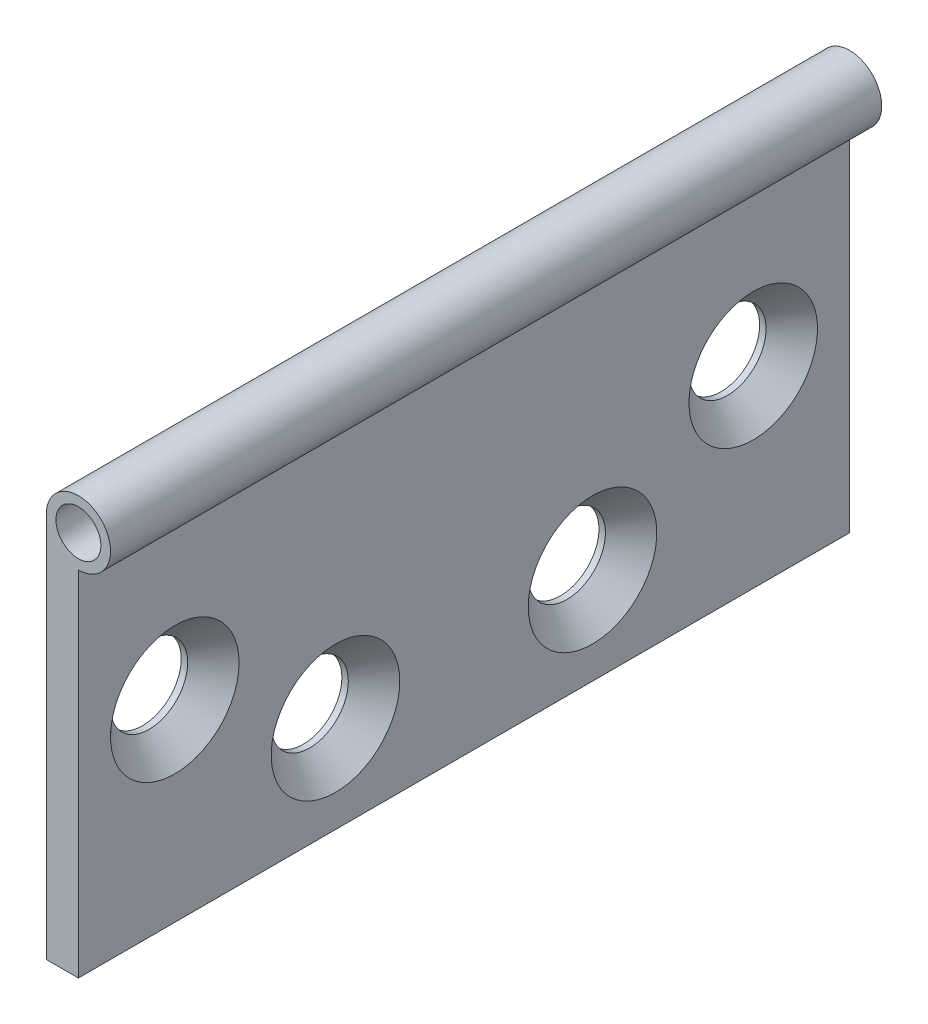
SolidWorks part; units mm, degrees
ref_plane "Спереди" through (0, 0, 0) normal (0, 0, 1) x (1, 0, 0)
ref_plane "Сверху" through (0, 0, 0) normal (0, 1, 0) x (1, 0, 0)
ref_plane "Справа" through (0, 0, 0) normal (1, 0, 0) x (0, 0, -1)
sketch "Эскиз1" plane through (0, 0, 0) normal (0, 0, 1) x (1, 0, 0)
  line L0 (0, 0) -> (0, 60)
  dimension "D1" = 60
extrude "Вытянуть-Тонкостенный2" add sketch "Эскиз1" along normal mid plane 120 thin contours L0
sketch "Эскиз2" plane through (0, 0, 60) normal (0, 0, 1) x (1, 0, 0)
  circle A0 centre (5, 60) radius 5
sweep "По траектории1" add profiles "Эскиз2" path edge at (0, 60, 0)
sketch "Эскиз3" plane through (0, 0, 60) normal (0, 0, 1) x (1, 0, 0)
  circle A0 centre (5, 60) radius 3.5
  dimension "D1" = 7
extrude "Вырез-Вытянуть1" cut sketch "Эскиз3" against normal through all
hole_wizard "Зенковка для  винта с плоской головкой M101" positions "Эскиз7" profile "Эскиз8" countersink size "M10" standard "Ansi Metric" end condition through all
sketch "Эскиз7" plane through (5, 0, 0) normal (1, 0, 0) x (0, 0, -1)
  line L0 (-60, 0) -> (-60, 55) construction
  line L1 (-60, 0) -> (60, 0) construction
  point P0 (-45, 30)
  point P2 (-20, 15)
  point P9 (0, 0)
  dimension "D1" = 15
  dimension "D2" = 30
  dimension "D3" = 40
  dimension "D4" = 15
sketch "Эскиз8" plane through (5, 30, 45) normal (0, 1, 0) x (0, 0, -1)
  line L0 (0, 0) -> (0, 5)
  line L1 (0, 5) -> (6, 5)
  line L2 (6, 5) -> (6, 4)
  line L3 (6, 4) -> (10, 0)
  line L5 (10, 0) -> (0, 0)
  line L6 (-6, 4) -> (-10, 0) construction
  line L11 (0, -6.35) -> (0, 107.95) construction
  dimension "Диаметр сквозного отверстия" = 12
  dimension "Глубина сквозного отверстия" = 5
  dimension "Диаметр передней зенковки" = 20
  dimension "Угол передней зенковки" = 90
mirror "Зеркальное отражение1" about plane through (0, 0, 0) normal (0, 0, 1) of "Зенковка для  винта с плоской головкой M101"
sketch "Эскиз10" plane through (5, 0, 0) normal (1, 0, 0) x (0, 0, -1)
  line L0 (-36, 54) -> (-36, 65)
  line L1 (60, 60) -> (60, 65) construction
  line L2 (-60, 54) -> (60, 54)
  line L3 (-60, 54) -> (60, 54)
  line L4 (60, 55) -> (60, 60) construction
  line L5 (-60, 65) -> (-60, 60) construction
  line L6 (-60, 60) -> (-60, 55) construction
  line L7 (60, 60) -> (60, 65)
  line L8 (60, 54) -> (60, 60)
  line L9 (-60, 65) -> (-60, 60)
  line L10 (-60, 60) -> (-60, 54)
  line L11 (-60, 65) -> (60, 65)
  line L12 (-12, 54) -> (-12, 65)
  line L13 (0, 0) -> (0, 65) construction
  line L14 (12, 54) -> (12, 65)
  line L15 (36, 54) -> (36, 65)
  dimension "D2" = 24
  dimension "D3" = 24
  dimension "D1" = 1
equation "\"depth\"= 5"
equation "\"width\"= 60"
equation "\"length\"= 120"
equation "\"D1@Вытянуть-Тонкостенный2\"= \"length\""
equation "\"D1@Эскиз1\"= \"width\""
equation "\"D5@Вытянуть-Тонкостенный2\"= \"depth\""
equation "\"D1@Эскиз3\"= \"depth\" / 5 * 7"
equation "\"D1@Эскиз7\"= \"length\" / 8"
equation "\"D2@Эскиз7\"= \"width\" / 2"
equation "\"D3@Эскиз7\"= \"length\" / 3"
equation "\"D4@Эскиз7\"= \"width\" / 4"
equation "\"D2@Эскиз10\"= \"length\" / 5"
equation "\"D3@Эскиз10\"= \"length\" / 5"
equation "\"D4@Эскиз4\"= \"length\" / 3"
equation "\"D3@Эскиз4\"= \"width\" / 2"
equation "\"D2@Эскиз4\"= \"width\" / 4"
equation "\"D1@Эскиз4\"= \"width\" / 4"
